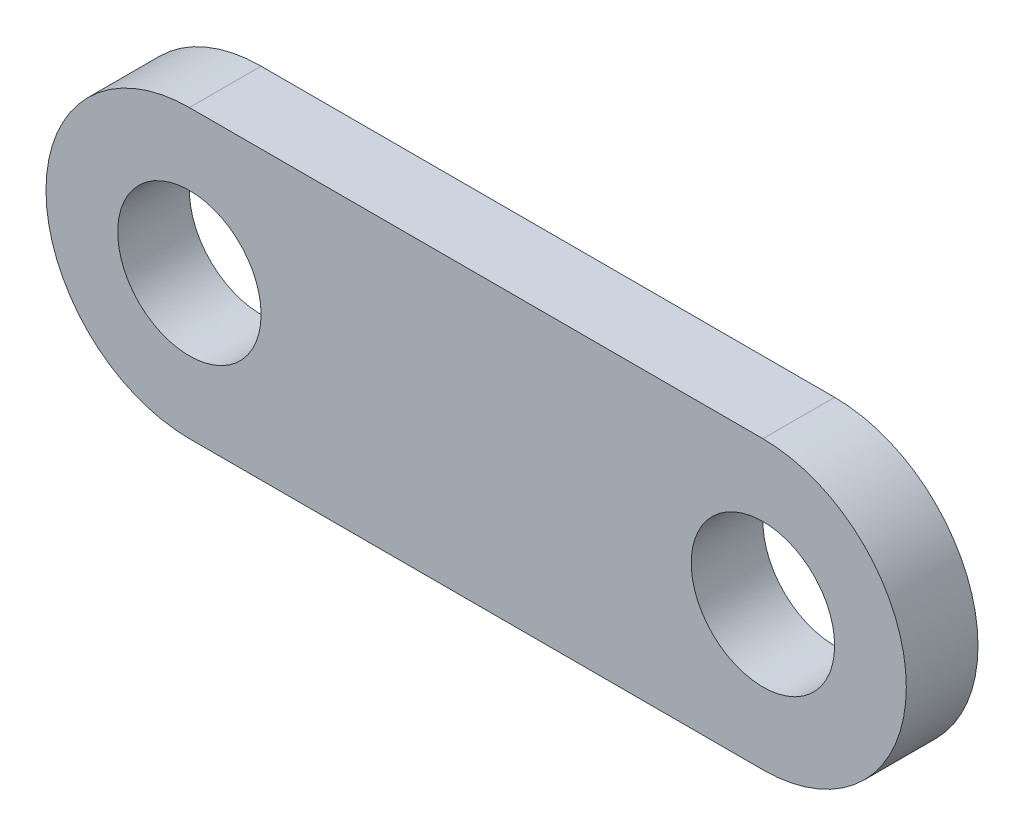
SolidWorks part; units mm, degrees
ref_plane "Front Plane" through (0, 0, 0) normal (0, 0, 1) x (1, 0, 0)
ref_plane "Top Plane" through (0, 0, 0) normal (0, 1, 0) x (1, 0, 0)
ref_plane "Right Plane" through (0, 0, 0) normal (1, 0, 0) x (0, 0, -1)
sketch "Sketch1" plane through (0, 0, 0) normal (0, 0, 1) x (1, 0, 0)
  line L0 (20, 0) -> (-20, 0) construction
  line L1 (20, -10) -> (-20, -10)
  line L2 (20, 10) -> (-20, 10)
  arc A0 (20, -10) -> (20, 10) centre (20, 0) ccw
  arc A1 (-20, 10) -> (-20, -10) centre (-20, 0) ccw
  circle A2 centre (-20, 0) radius 5
  circle A3 centre (20, 0) radius 5
  point P2 (0, 0)
  dimension "D1" = 40
  dimension "D2" = 20
extrude "Boss-Extrude1" add sketch "Sketch1" along normal blind 5
